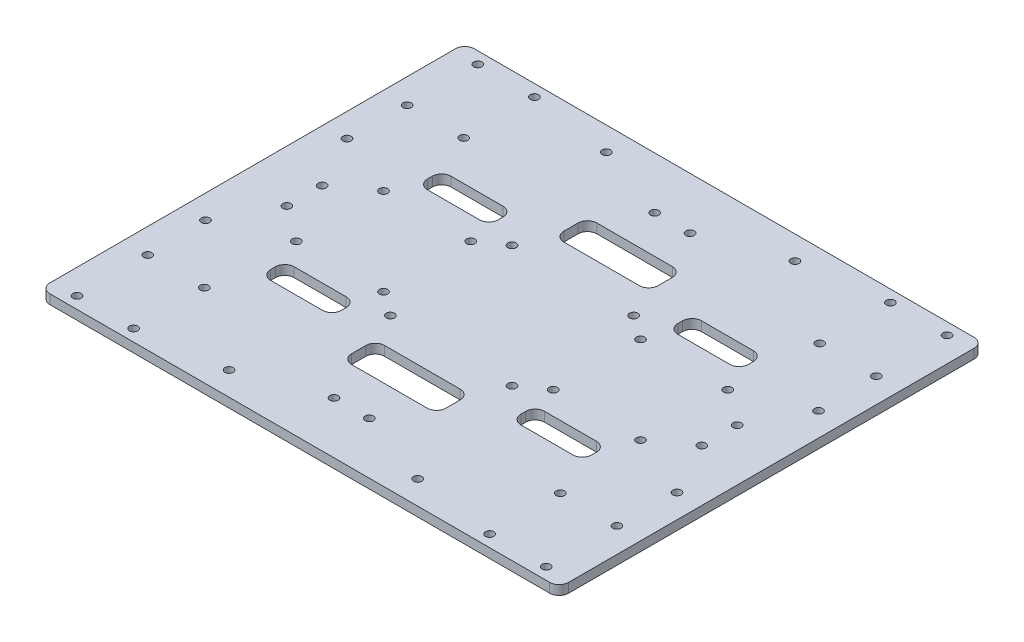
SolidWorks part; units mm, degrees
ref_plane "前视基准面" through (0, 0, 0) normal (0, 0, 1) x (1, 0, 0)
ref_plane "上视基准面" through (0, 0, 0) normal (0, 1, 0) x (1, 0, 0)
ref_plane "右视基准面" through (0, 0, 0) normal (1, 0, 0) x (0, 0, -1)
sketch "草图1" plane through (0, 0, 0) normal (0, 1, 0) x (1, 0, 0)
  line L1 (110, 90) -> (-110, 90)
  line L2 (110, 90) -> (110, -90)
  line L3 (110, -90) -> (-110, -90)
  line L4 (-110, 90) -> (-110, -90)
  line L5 (110, 90) -> (-110, -90) construction
  line L6 (110, -90) -> (-110, 90) construction
  point P0 (0, 0)
  dimension "D1" = 180
  dimension "D2" = 220
extrude "凸台-拉伸1" add sketch "草图1" along normal blind 4
sketch "草图3" plane through (0, 0, 0) normal (0, -1, 0) x (1, 0, 0)
  circle A0 centre (-99.5, -55) radius 1.75
  circle A1 centre (-75.5, -55) radius 1.75
  circle A2 centre (-99.5, -85) radius 1.75
  circle A3 centre (-75.5, -85) radius 1.75
  circle A4 centre (75.5, -55) radius 1.75
  circle A5 centre (99.5, -55) radius 1.75
  circle A6 centre (75.5, -85) radius 1.75
  circle A7 centre (99.5, -85) radius 1.75
  circle A8 centre (-99.5, 85) radius 1.75
  circle A9 centre (-75.5, 85) radius 1.75
  circle A10 centre (-99.5, 55) radius 1.75
  circle A11 centre (-75.5, 55) radius 1.75
  circle A12 centre (75.5, 85) radius 1.75
  circle A13 centre (99.5, 85) radius 1.75
  circle A14 centre (75.5, 55) radius 1.75
  circle A15 centre (99.5, 55) radius 1.75
  circle A16 centre (-88, 7.5) radius 1.75
  circle A17 centre (-88, -7.5) radius 1.75
  circle A18 centre (-7.5, -68) radius 1.75
  circle A19 centre (7.5, -68) radius 1.75
  circle A20 centre (88, -7.5) radius 1.75
  circle A21 centre (88, 7.5) radius 1.75
  circle A22 centre (-7.5, 68) radius 1.75
  circle A23 centre (7.5, 68) radius 1.75
extrude "切除-拉伸2" cut sketch "草图3" against normal blind 4
sketch "草图4" plane through (0, 0, 0) normal (0, -1, 0) x (1, 0, 0)
  circle A0 centre (-73, 18.5) radius 1.75
  circle A1 centre (-36, 18.5) radius 1.75
  circle A2 centre (-73, -18.5) radius 1.75
  circle A3 centre (-36, -18.5) radius 1.75
  circle A4 centre (36, 18.5) radius 1.75
  circle A5 centre (73, 18.5) radius 1.75
  circle A6 centre (36, -18.5) radius 1.75
  circle A8 centre (73, -18.5) radius 1.75
  circle A9 centre (-25.8, 25.8) radius 1.75
  circle A10 centre (25.8, 25.8) radius 1.75
  circle A11 centre (-25.8, -25.8) radius 1.75
  circle A12 centre (25.8, -25.8) radius 1.75
extrude "切除-拉伸3" cut sketch "草图4" against normal blind 4 contours A5 | A8 | A6 | A4 | A1 | A0 | A3 | A2 | A10 | A9 | A11 | A12
sketch "草图5" plane through (0, 0, 0) normal (0, -1, 0) x (1, 0, 0)
  circle A0 centre (-40, 80) radius 1.75
  circle A1 centre (40, 80) radius 1.75
  circle A2 centre (100, 30) radius 1.75
  circle A3 centre (100, -30) radius 1.75
  circle A4 centre (40, -80) radius 1.75
  circle A5 centre (-40, -80) radius 1.75
  circle A6 centre (-100, -30) radius 1.75
  circle A7 centre (-100, 30) radius 1.75
extrude "切除-拉伸4" cut sketch "草图5" against normal blind 4
fillet "圆角1" radius 4 4 edges at (-110, 2, 90) (110, 2, 90) (110, 2, -90) (-110, 2, -90)
sketch "草图6" plane through (0, 0, 0) normal (0, -1, 0) x (1, 0, 0)
  line L0 (-119.6059, 0) -> (120.4283, 0) construction
  line L1 (0, 96.3639) -> (0, -96.6931) construction
  line L2 (-106, 90) -> (106, 90) construction
  line L3 (-20, 38) -> (20, 38)
  line L4 (-20, 38) -> (-20, 52)
  line L5 (-20, 52) -> (20, 52)
  line L6 (20, 38) -> (20, 52)
  line L7 (-20, 38) -> (20, 52) construction
  line L8 (-20, 52) -> (20, 38) construction
  line L9 (68.0941, 38.2699) -> (38.0941, 28.2699) construction
  line L10 (-68.0941, 28.2699) -> (-38.0941, 28.2699)
  line L11 (-68.0941, 28.2699) -> (-68.0941, 38.2699)
  line L12 (-68.0941, 38.2699) -> (-38.0941, 38.2699)
  line L13 (-38.0941, 28.2699) -> (-38.0941, 38.2699)
  line L14 (-68.0941, 28.2699) -> (-38.0941, 38.2699) construction
  line L15 (-68.0941, 38.2699) -> (-38.0941, 28.2699) construction
  line L16 (68.0941, 28.2699) -> (38.0941, 38.2699) construction
  line L17 (38.0941, 28.2699) -> (38.0941, 38.2699)
  line L18 (68.0941, 38.2699) -> (38.0941, 38.2699)
  line L19 (68.0941, 28.2699) -> (68.0941, 38.2699)
  line L20 (68.0941, 28.2699) -> (38.0941, 28.2699)
  line L21 (68.0941, -28.2699) -> (38.0941, -38.2699) construction
  line L22 (-68.0941, -38.2699) -> (-38.0941, -28.2699) construction
  line L23 (-68.0941, -28.2699) -> (-38.0941, -38.2699) construction
  line L24 (68.0941, -38.2699) -> (38.0941, -28.2699) construction
  line L25 (-20, -52) -> (20, -38) construction
  line L26 (-20, -38) -> (20, -52) construction
  line L27 (68.0941, -28.2699) -> (38.0941, -28.2699)
  line L28 (68.0941, -28.2699) -> (68.0941, -38.2699)
  line L29 (68.0941, -38.2699) -> (38.0941, -38.2699)
  line L30 (38.0941, -28.2699) -> (38.0941, -38.2699)
  line L31 (-38.0941, -28.2699) -> (-38.0941, -38.2699)
  line L32 (-68.0941, -38.2699) -> (-38.0941, -38.2699)
  line L33 (-68.0941, -28.2699) -> (-68.0941, -38.2699)
  line L34 (-68.0941, -28.2699) -> (-38.0941, -28.2699)
  line L35 (20, -38) -> (20, -52)
  line L36 (-20, -52) -> (20, -52)
  line L37 (-20, -38) -> (-20, -52)
  line L38 (-20, -38) -> (20, -38)
  point P5 (0, 45)
  point P10 (-53.0941, 33.2699)
  point P17 (-53.0941, 33.2699)
  point P22 (53.0941, 33.2699)
  point P35 (53.0941, -33.2699)
  point P36 (-53.0941, -33.2699)
  point P37 (0, -45)
  dimension "D1" = 14
  dimension "D2" = 45
  dimension "D3" = 40
  dimension "D4" = 30
  dimension "D5" = 10
extrude "切除-拉伸5" cut sketch "草图6" against normal blind 4
fillet "圆角2" radius 4 24 edges at (-68.0941, 2, -28.2699) (-38.0941, 2, -38.2699) (-68.0941, 2, -38.2699) (-38.0941, 2, -28.2699) (68.0941, 2, -28.2699) (38.0941, 2, -38.2699) (38.0941, 2, -28.2699) (68.0941, 2, -38.2699) (20, 2, -52) (-20, 2, -52) (-20, 2, -38) (20, 2, -38) (68.0941, 2, 38.2699) (38.0941, 2, 38.2699) (38.0941, 2, 28.2699) (68.0941, 2, 28.2699) (20, 2, 38) (-20, 2, 38) (20, 2, 52) (-20, 2, 52) (-38.0941, 2, 28.2699) (-68.0941, 2, 28.2699) (-38.0941, 2, 38.2699) (-68.0941, 2, 38.2699)
